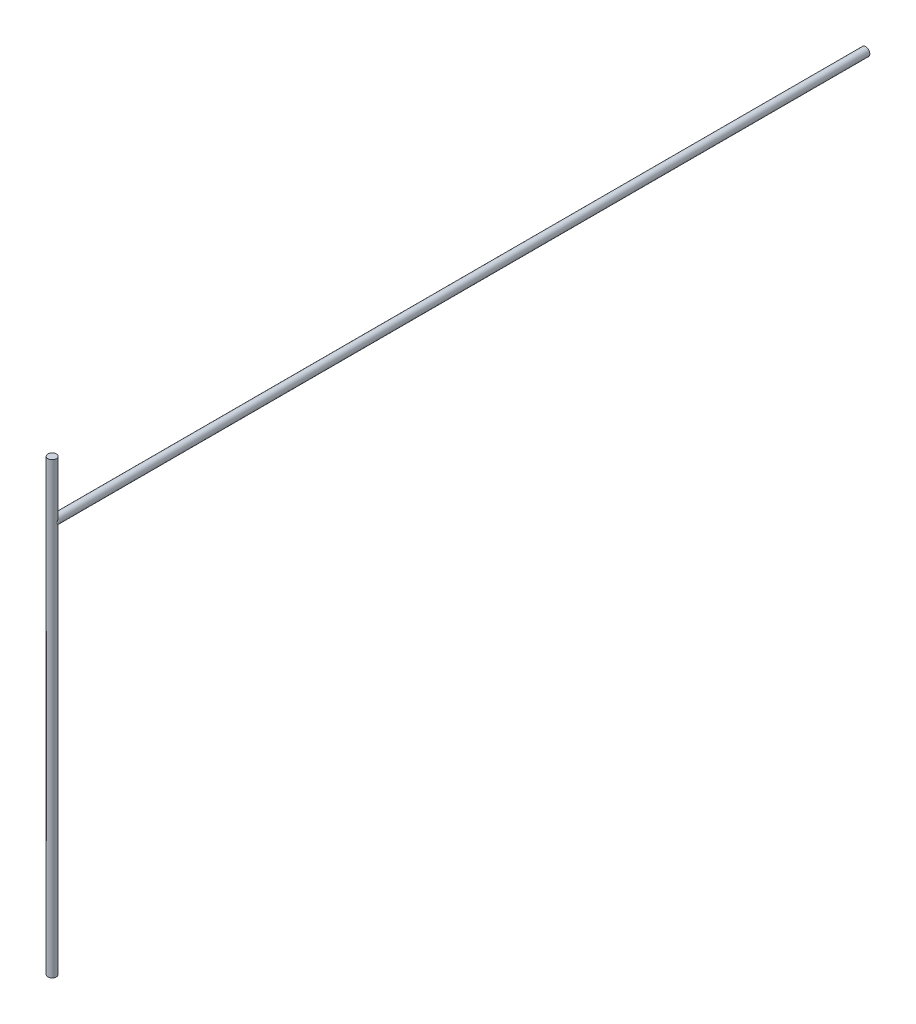
SolidWorks part; units mm, degrees
ref_plane "前视基准面" through (0, 0, 0) normal (0, 0, 1) x (1, 0, 0)
ref_plane "上视基准面" through (0, 0, 0) normal (0, 1, 0) x (1, 0, 0)
ref_plane "右视基准面" through (0, 0, 0) normal (1, 0, 0) x (0, 0, -1)
sketch "草图1" plane through (0, 0, 0) normal (0, 0, 1) x (1, 0, 0)
  circle A0 centre (0, 0) radius 0.75
  dimension "D1" = 1.5
extrude "凸台-拉伸1" add sketch "草图1" along normal blind 145
sketch "草图2" plane through (0, 0, 0) normal (0, 1, 0) x (1, 0, 0)
  circle A0 centre (0, 0) radius 0.75
  dimension "D1" = 1.5
extrude "凸台-拉伸2" add sketch "草图2" along normal blind 10 and the other way blind 70
move or copy body "实体-移动/复制1" bodies to move or copy 107 copy no rotation origin (0, 0, 0) rotation axis (0, 1, 0) rotation angle 180
